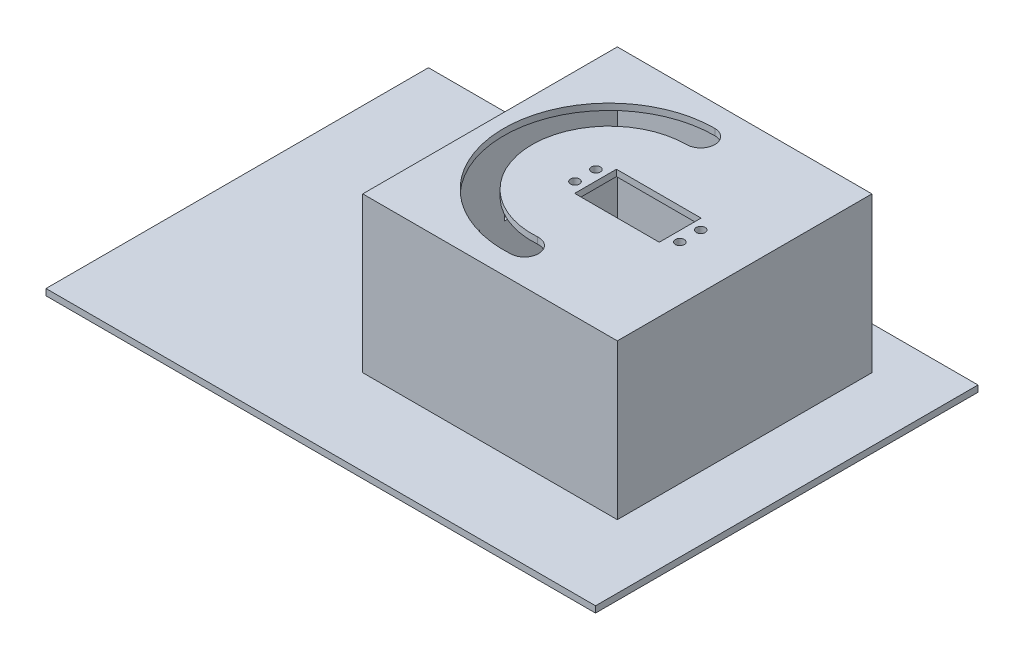
SolidWorks part; units mm, degrees
ref_plane "Front Plane" through (0, 0, 0) normal (0, 0, 1) x (1, 0, 0)
ref_plane "Top Plane" through (0, 0, 0) normal (0, 1, 0) x (1, 0, 0)
ref_plane "Right Plane" through (0, 0, 0) normal (1, 0, 0) x (0, 0, -1)
sketch "Sketch1" plane through (0, 0, 0) normal (0, 1, 0) x (1, 0, 0)
  line L1 (-70, -80) -> (70, -80)
  line L2 (-70, -80) -> (-70, 80)
  line L3 (-70, 80) -> (70, 80)
  line L4 (70, -80) -> (70, 80)
  line L5 (-70, -80) -> (70, 80) construction
  line L6 (-70, 80) -> (70, -80) construction
  point P0 (0, 0)
  dimension "D1" = 140
  dimension "D2" = 160
extrude "Boss-Extrude1" add sketch "Sketch1" along normal blind 3
sketch "Sketch2" plane through (0, 3, 0) normal (0, 1, 0) x (1, 0, 0)
  line L1 (-58.5, -58.5) -> (58.5, -58.5)
  line L2 (-58.5, -58.5) -> (-58.5, 58.5)
  line L3 (-58.5, 58.5) -> (58.5, 58.5)
  line L4 (58.5, -58.5) -> (58.5, 58.5)
  line L5 (-58.5, -58.5) -> (58.5, 58.5) construction
  line L6 (-58.5, 58.5) -> (58.5, -58.5) construction
  line L7 (60, -60) -> (-60, -60)
  line L8 (60, -60) -> (60, 60)
  line L9 (60, 60) -> (-60, 60)
  line L10 (-60, -60) -> (-60, 60)
  line L11 (60, -60) -> (-60, 60) construction
  line L12 (60, 60) -> (-60, -60) construction
  point P0 (0, 0)
  point P6 (0, 0)
  dimension "D1" = 117
  dimension "D2" = 117
  dimension "D3" = 120
extrude "Boss-Extrude2" add sketch "Sketch2" along normal blind 70
sketch "Sketch4" plane through (0, 73, 0) normal (0, 1, 0) x (1, 0, 0)
  line L1 (-60, 60) -> (60, 60)
  line L2 (-60, 60) -> (-60, -60)
  line L3 (-60, -60) -> (60, -60)
  line L4 (60, 60) -> (60, -60)
  dimension "D1" = 120
  dimension "D2" = 120
extrude "Boss-Extrude4" add sketch "Sketch4" along normal blind 3
sketch "Sketch5" plane through (0, 76, 0) normal (0, 1, 0) x (1, 0, 0)
  line L0 (-60, 60) -> (60, -60) construction
  line L1 (-10.27, -9.855) -> (29.63, -9.855)
  line L2 (-10.27, -9.855) -> (-10.27, 9.855)
  line L3 (-10.27, 9.855) -> (29.63, 9.855)
  line L4 (29.63, -9.855) -> (29.63, 9.855)
  line L5 (-10.27, -9.855) -> (29.63, 9.855) construction
  line L6 (-10.27, 9.855) -> (29.63, -9.855) construction
  line L7 (60, -60) -> (60, 60) construction
  line L8 (60, -60) -> (60, 60) construction
  line L9 (60, -60) -> (60, 60) construction
  line L10 (60, 60) -> (-60, 60) construction
  line L11 (60, 60) -> (-60, -60) construction
  circle A1 centre (34.39, -4.925) radius 2.1
  circle A2 centre (34.39, 4.925) radius 2.1
  circle A4 centre (-15.03, -4.925) radius 2.1
  circle A5 centre (-15.03, 4.925) radius 2.1
  point P3 (9.68, 0)
  dimension "D2" = 4.2
  dimension "D6" = 9.85
  dimension "D7" = 4.93
  dimension "D8" = 4.93
  dimension "D9" = 4.93
  dimension "D10" = 9.68
  dimension "D11" = 4.93
  dimension "D12" = 4.93
  dimension "D1" = 39.9
  dimension "D3" = 19.71
  dimension "D4" = 4.76
  dimension "D5" = 4.76
extrude "Cut-Extrude2" cut sketch "Sketch5" against normal blind 3
sketch "Sketch6" plane through (0, 76, 0) normal (0, 1, 0) x (1, 0, 0)
  line L1 (9.1491, -8.655) -> (-9.1491, -8.655)
  line L2 (9.1491, -8.655) -> (9.1491, 8.655)
  line L3 (9.1491, 8.655) -> (-9.1491, 8.655)
  line L4 (-9.1491, -8.655) -> (-9.1491, 8.655)
  line L5 (9.1491, -8.655) -> (-9.1491, 8.655) construction
  line L6 (9.1491, 8.655) -> (-9.1491, -8.655) construction
  point P0 (0, 0)
extrude "Cut-Extrude3" cut sketch "Sketch6" against normal blind 3
sketch "Sketch7" plane through (0, 0, 0) normal (0, 1, 0) x (1, 0, 0)
  line L1 (-45, -45) -> (45, -45)
  line L2 (-45, -45) -> (-45, 45)
  line L3 (-45, 45) -> (45, 45)
  line L4 (45, -45) -> (45, 45)
  line L5 (-45, -45) -> (45, 45) construction
  line L6 (-45, 45) -> (45, -45) construction
  point P0 (0, 0)
  dimension "D1" = 90
  dimension "D2" = 90
sketch "Sketch13" plane through (0, 76, 0) normal (0, 1, 0) x (1, 0, 0)
  arc A0 (-3.7926, 43.0768) -> (-0.8101, -42.9734) centre (-3.7926, 0) ccw construction
  arc A1 (-3.7926, 49.7288) -> (-0.3495, -49.6094) centre (-3.7926, 0) ccw
  arc A2 (-3.7926, 36.4249) -> (-1.2706, -36.3375) centre (-3.7926, 0) ccw
  arc A3 (-3.7926, 36.4249) -> (-3.7926, 49.7288) centre (-3.7926, 43.0768) ccw
  arc A4 (-0.3495, -49.6094) -> (-1.2706, -36.3375) centre (-0.8101, -42.9734) ccw
  point P3 (-46.8436, -1.4922)
extrude "Cut-Extrude8" cut sketch "Sketch13" against normal blind 5
sketch "Sketch15" plane through (0, 3, 0) normal (0, 1, 0) x (1, 0, 0)
  line L0 (70, 80) -> (-70, 80) construction
  line L1 (90, 80) -> (-169.0216, 80)
  line L2 (90, 80) -> (90, -100.2694)
  line L3 (90, -100.2694) -> (-169.0216, -100.2694)
  line L4 (-169.0216, 80) -> (-169.0216, -100.2694)
extrude "Boss-Extrude5" add sketch "Sketch15" against normal blind 3
sketch "Sketch18" plane through (0, 3, 0) normal (0, 1, 0) x (1, 0, 0)
  circle A0 centre (-55.452, -27.2274) radius 1.6 construction
  circle A1 centre (-55.452, -27.2274) radius 1.6
  circle A2 centre (-55.452, 32.2086) radius 1.6 construction
  circle A3 centre (-55.452, 32.2086) radius 1.6
  circle A4 centre (4.746, 32.2086) radius 1.6 construction
  circle A5 centre (4.746, 32.2086) radius 1.6
  circle A6 centre (4.746, -27.2274) radius 1.6 construction
  circle A7 centre (4.746, -27.2274) radius 1.6
extrude "Cut-Extrude9" cut sketch "Sketch18" against normal blind 10
sketch "Sketch19" plane through (-60, 0, 0) normal (-1, 0, 0) x (0, 0, 1)
  line L0 (12.3674, 3) -> (12.3674, 33) construction
  line L1 (-60, 3) -> (60, 3) construction
  line L2 (-5.6466, 31.35) -> (-5.6466, 26.9) construction
  line L3 (6.3674, 30.75) -> (18.3674, 30.75)
  line L4 (6.3674, 30.75) -> (6.3674, 35.25)
  line L5 (6.3674, 35.25) -> (18.3674, 35.25)
  line L6 (18.3674, 30.75) -> (18.3674, 35.25)
  line L7 (6.3674, 30.75) -> (18.3674, 35.25) construction
  line L8 (6.3674, 35.25) -> (18.3674, 30.75) construction
  line L9 (-5.2594, 33) -> (-5.2594, 41.4) construction
  line L10 (-5.2594, 33) -> (-17.2594, 33) construction
  line L11 (-5.2594, 41.4) -> (-17.2594, 41.4) construction
  line L12 (-17.2594, 33) -> (-17.2594, 41.4) construction
  line L13 (-33.6488, 33.0619) -> (-23.5648, 33.0619) construction
  line L14 (-28.1126, 38.85) -> (-28.1126, 27.45) construction
  line L15 (-23.5648, 40.424) -> (-23.5648, 33.0619) construction
  line L16 (-33.6488, 40.424) -> (-23.5648, 40.424) construction
  line L17 (-33.6488, 40.424) -> (-33.6488, 33.0619) construction
  line L18 (-5.2594, 33) -> (-5.2594, 41.4)
  line L19 (-5.2594, 33) -> (-17.2594, 33)
  line L20 (-5.2594, 41.4) -> (-17.2594, 41.4)
  line L21 (-17.2594, 33) -> (-17.2594, 41.4)
  line L22 (-33.6488, 33.0619) -> (-23.5648, 33.0619)
  line L23 (-28.1126, 38.85) -> (-28.1126, 27.45)
  line L24 (-23.5648, 40.424) -> (-23.5648, 33.0619)
  line L25 (-33.6488, 40.424) -> (-23.5648, 40.424)
  line L26 (-33.6488, 40.424) -> (-33.6488, 33.0619)
  dimension "D1" = 14.86
  dimension "D2" = 30
  dimension "D3" = 4.5
  dimension "D4" = 90
  dimension "D5" = 12
extrude "Cut-Extrude11" cut sketch "Sketch19" against normal blind 5
